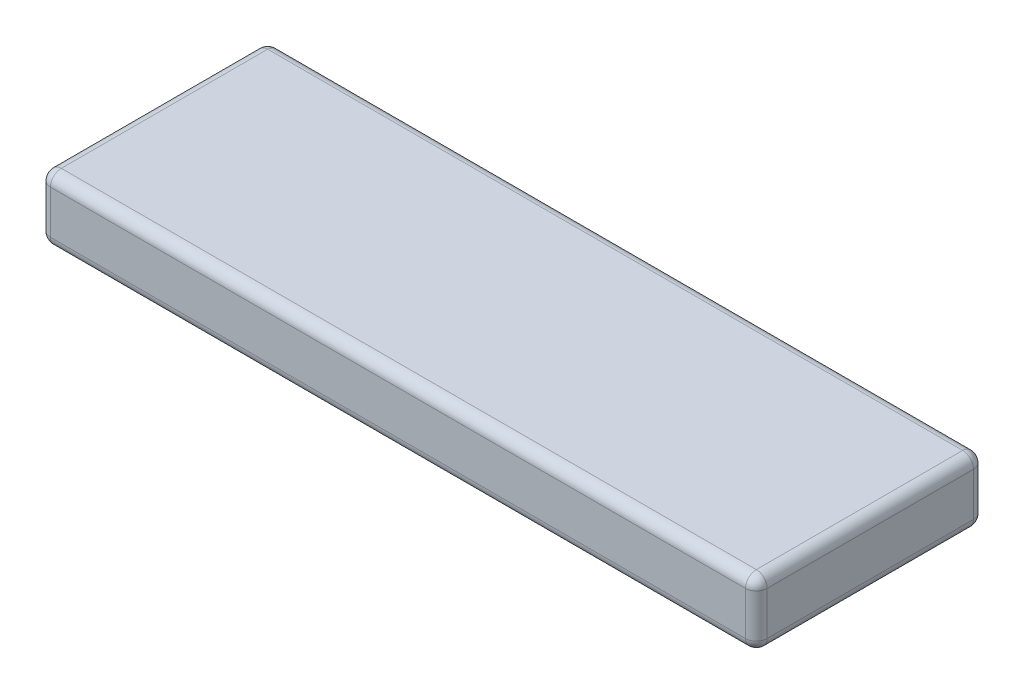
SolidWorks part; units mm, degrees
ref_plane "Front Plane" through (0, 0, 0) normal (0, 0, 1) x (1, 0, 0)
ref_plane "Top Plane" through (0, 0, 0) normal (0, 1, 0) x (1, 0, 0)
ref_plane "Right Plane" through (0, 0, 0) normal (1, 0, 0) x (0, 0, -1)
sketch "Sketch1" plane through (0, 0, 0) normal (0, 1, 0) x (1, 0, 0)
  line L1 (-66, -21) -> (66, -21)
  line L2 (-66, -21) -> (-66, 21)
  line L3 (-66, 21) -> (66, 21)
  line L4 (66, -21) -> (66, 21)
  line L5 (-66, -21) -> (66, 21) construction
  line L6 (-66, 21) -> (66, -21) construction
  point P0 (0, 0)
  dimension "D1" = 132
  dimension "D2" = 42
extrude "Boss-Extrude1" add sketch "Sketch1" along normal blind 12
fillet "Fillet1" radius 2 12 edges at (-66, 0, 0) (66, 0, 0) (66, 6, -21) (-66, 6, -21) (0, 0, -21) (-66, 6, 21) (66, 6, 21) (0, 0, 21) (0, 12, 21) (-66, 12, 0) (0, 12, -21) (66, 12, 0)
